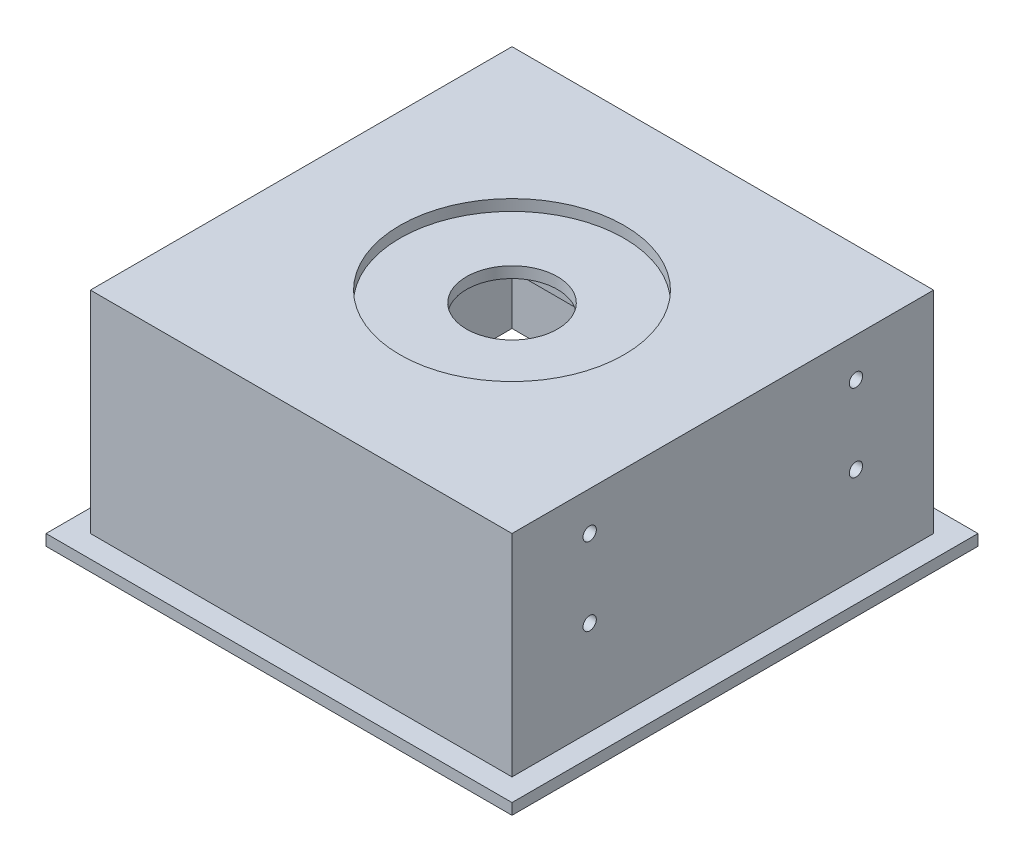
SolidWorks part; units mm, degrees
material "ABS"
ref_plane "Front Plane" through (0, 0, 0) normal (0, 0, 1) x (1, 0, 0)
ref_plane "Top Plane" through (0, 0, 0) normal (0, 1, 0) x (1, 0, 0)
ref_plane "Right Plane" through (0, 0, 0) normal (1, 0, 0) x (0, 0, -1)
sketch "Sketch1" plane through (0, 0, 0) normal (0, 1, 0) x (1, 0, 0)
  line L1 (0, 0) -> (-210, 0)
  line L2 (0, 0) -> (0, 210)
  line L3 (0, 210) -> (-210, 210)
  line L4 (-210, 0) -> (-210, 210)
  dimension "D1" = 210
  dimension "D2" = 210
extrude "Boss-Extrude1" add sketch "Sketch1" along normal blind 5
sketch "Sketch2" plane through (0, 5, 0) normal (0, 1, 0) x (1, 0, 0)
  line L0 (0, 210) -> (-210, 210) construction
  line L1 (-200, 200) -> (-10, 200)
  line L2 (-200, 200) -> (-200, 10)
  line L3 (-200, 10) -> (-10, 10)
  line L4 (-10, 200) -> (-10, 10)
  line L5 (-210, 0) -> (0, 0) construction
  line L6 (0, 0) -> (0, 210) construction
  line L7 (-210, 210) -> (-210, 0) construction
  dimension "D1" = 10
  dimension "D2" = 10
  dimension "D3" = 10
  dimension "D4" = 10
extrude "Boss-Extrude2" add sketch "Sketch2" along normal blind 95
sketch "Sketch3" plane through (0, 0, 0) normal (0, -1, 0) x (-1, 0, 0)
  line L0 (210, 210) -> (210, 0) construction
  line L1 (190, 20) -> (20, 20)
  line L2 (190, 20) -> (190, 190)
  line L3 (190, 190) -> (20, 190)
  line L4 (20, 20) -> (20, 190)
  line L5 (0, 0) -> (0, 210) construction
  line L6 (210, 0) -> (0, 0) construction
  line L7 (0, 210) -> (210, 210) construction
  dimension "D1" = 20
  dimension "D2" = 20
  dimension "D3" = 20
  dimension "D4" = 20
extrude "Cut-Extrude1" cut sketch "Sketch3" against normal blind 90
sketch "Sketch4" plane through (0, 100, 0) normal (0, 1, 0) x (1, 0, 0)
  line L1 (-10, 10) -> (-10, 200) construction
  line L2 (-10, 200) -> (-200, 200) construction
  circle A0 centre (-105, 105) radius 50.5
  dimension "D3" = 101
  dimension "D1" = 95
  dimension "D2" = 95
extrude "Cut-Extrude2" cut sketch "Sketch4" against normal blind 5
sketch "Sketch5" plane through (0, 95, 0) normal (0, 1, 0) x (1, 0, 0)
  circle A0 centre (-105, 105) radius 20.5
  circle A3 centre (-105, 105) radius 50.5 construction
  dimension "D1" = 41
extrude "Cut-Extrude3" cut sketch "Sketch5" against normal blind 5
sketch "Sketch6" plane through (0, 90, 0) normal (0, -1, 0) x (1, 0, 0)
  line L0 (-20, -20) -> (-190, -20) construction
  line L1 (-75, -80) -> (-135, -80)
  line L2 (-75, -80) -> (-75, -95)
  line L3 (-75, -95) -> (-135, -95)
  line L4 (-135, -80) -> (-135, -95)
  line L5 (-20, -190) -> (-20, -20) construction
  line L8 (-75, -135) -> (-135, -135)
  line L9 (-75, -135) -> (-75, -150)
  line L10 (-75, -150) -> (-135, -150)
  line L11 (-135, -135) -> (-135, -150)
  dimension "D1" = 75
  dimension "D2" = 15
  dimension "D3" = 60
  dimension "D4" = 55
  dimension "D5" = 15
  dimension "D6" = 40
  dimension "D7" = 55
  dimension "D8" = 60
extrude "Boss-Extrude3" add sketch "Sketch6" along normal blind 12.5
sketch "Sketch7" plane through (0, 0, -95) normal (0, 0, -1) x (-1, 0, 0)
  line L0 (135, 90) -> (122.8955, 90) construction
  line L1 (130, 90) -> (80, 90)
  line L2 (130, 90) -> (130, 82.5)
  line L3 (130, 82.5) -> (80, 82.5)
  line L4 (80, 90) -> (80, 82.5)
  line L5 (135, 77.5) -> (135, 90) construction
  line L6 (75, 77.5) -> (75, 90) construction
  dimension "D1" = 7.5
  dimension "D2" = 5
  dimension "D3" = 5
extrude "Cut-Extrude4" cut sketch "Sketch7" against normal blind 12.5
sketch "Sketch8" plane through (0, 77.5, 0) normal (0, -1, 0) x (1, 0, 0)
  circle A0 centre (-100, -89.8) radius 2
  circle A1 centre (-110, -89.8) radius 2
  circle A2 centre (-110, -140.2) radius 2
  circle A3 centre (-100, -140.2) radius 2
extrude "Cut-Extrude5" cut sketch "Sketch8" against normal blind 7.5
sketch "Sketch9" plane through (-10, 0, 0) normal (1, 0, 0) x (0, 0, -1)
  circle A0 centre (165, 47.5) radius 3
  circle A1 centre (45, 47.5) radius 3
  circle A2 centre (45, 82.5) radius 3
  circle A3 centre (165, 82.5) radius 3
extrude "Cut-Extrude6" cut sketch "Sketch9" against normal blind 7.5
